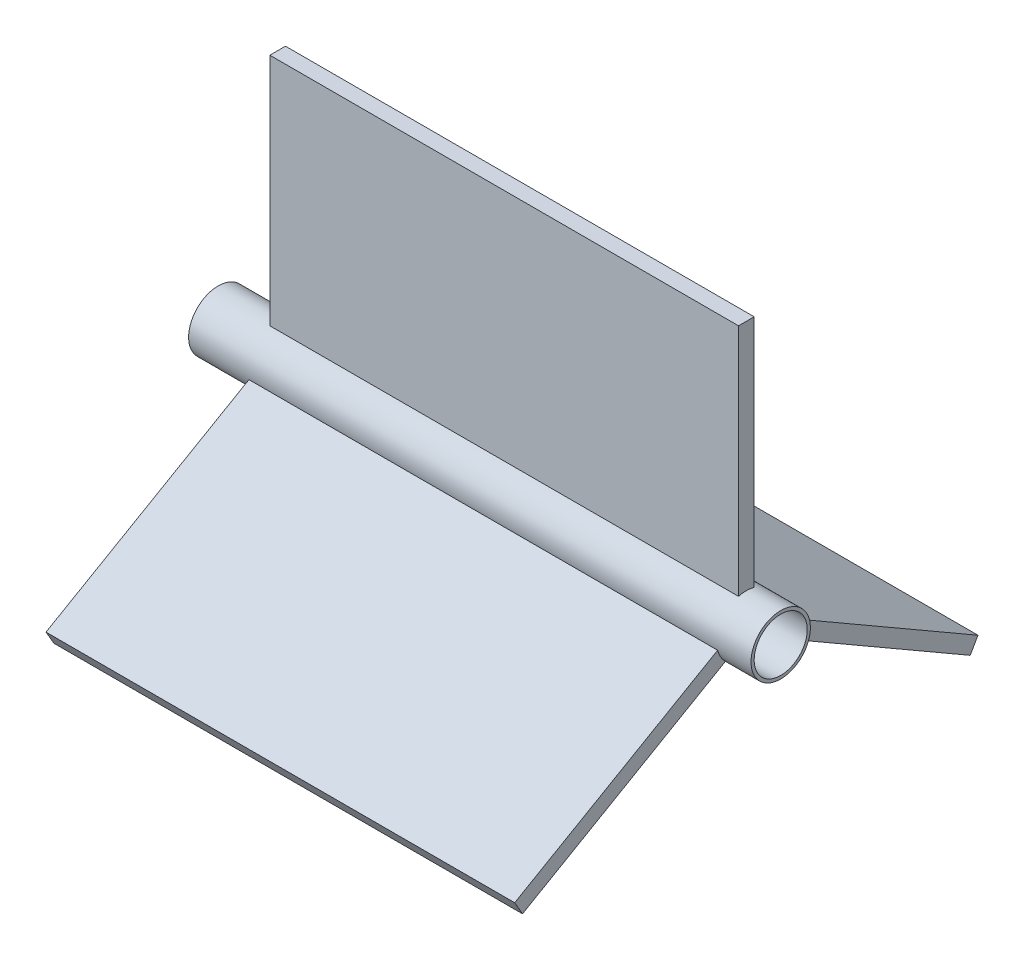
SolidWorks part; units mm, degrees
ref_plane "Alzado" through (0, 0, 0) normal (0, 0, 1) x (1, 0, 0)
ref_plane "Planta" through (0, 0, 0) normal (0, 1, 0) x (1, 0, 0)
ref_plane "Vista lateral" through (0, 0, 0) normal (1, 0, 0) x (0, 0, -1)
sketch "Croquis1" plane through (0, 0, 0) normal (1, 0, 0) x (0, 0, -1)
  circle A0 centre (0, 0) radius 9.5
  dimension "D1" = 19
extrude "Saliente-Extruir1" add sketch "Croquis1" along normal blind 180
ref_plane "Plano1" through (169, 0, 0) normal (1, 0, 0) x (0, 0, -1)
sketch "Croquis2" plane through (0, 0, 0) normal (-1, 0, 0) x (0, 0, 1)
  line L0 (74.1392, -39.9175) -> (71.6392, -44.2476)
  line L1 (-2.5, 9.1652) -> (2.5, 9.1652)
  line L2 (-2.5, 9.1652) -> (-2.5, 84.1652)
  line L3 (-2.5, 84.1652) -> (2.5, 84.1652)
  line L4 (2.5, 9.1652) -> (2.5, 84.1652)
  line L5 (-2.5, 9.1652) -> (2.5, 84.1652) construction
  line L6 (-2.5, 84.1652) -> (2.5, 9.1652) construction
  line L7 (6.6873, -6.7476) -> (71.6392, -44.2476)
  line L8 (9.1873, -2.4175) -> (74.1392, -39.9175)
  line L9 (9.1873, -2.4175) -> (6.6873, -6.7476)
  line L10 (-71.6392, -44.2476) -> (-74.1392, -39.9175)
  line L11 (-9.1873, -2.4175) -> (-74.1392, -39.9175)
  line L12 (-6.6873, -6.7476) -> (-71.6392, -44.2476)
  line L13 (-6.6873, -6.7476) -> (-9.1873, -2.4175)
  circle A0 centre (0, 0) radius 9.5 construction
  point P4 (0, 46.6652)
  point P18 (0, 0)
  dimension "D1" = 5
  dimension "D2" = 75
  dimension "D3" = 3
extrude "Saliente-Extruir2" add sketch "Croquis2" along normal blind 150 from surface at -169 starting at plane "Plano1"
sketch "Croquis3" plane through (0, 0, 0) normal (-1, 0, 0) x (0, 0, 1)
  circle A0 centre (0, 0) radius 8.5
  circle A1 centre (0, 0) radius 9.5 construction
  dimension "D1" = 1
extrude "Cortar-Extruir1" cut sketch "Croquis3" against normal through all
equation "\"D2@Croquis2\"=75"
